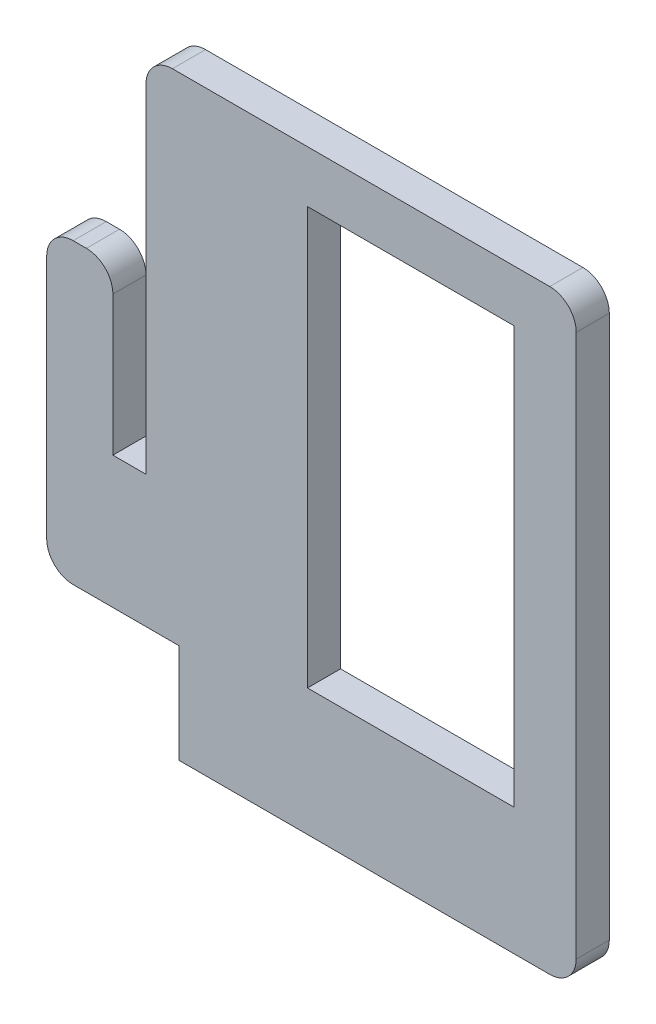
SolidWorks part; units mm, degrees
ref_plane "Front Plane" through (0, 0, 0) normal (0, 0, 1) x (1, 0, 0)
ref_plane "Top Plane" through (0, 0, 0) normal (0, 1, 0) x (1, 0, 0)
ref_plane "Right Plane" through (0, 0, 0) normal (1, 0, 0) x (0, 0, -1)
sketch "Sketch1" plane through (0, 0, 0) normal (0, 0, 1) x (1, 0, 0)
  line L1 (12.7, 0) -> (50.8, 0)
  line L2 (0, 9.525) -> (0, 38.1)
  line L3 (0, 38.1) -> (6.35, 38.1)
  line L4 (50.8, 0) -> (50.8, 38.1)
  line L5 (25.019, 52.1772) -> (44.831, 52.1772)
  line L6 (6.35, 38.1) -> (6.35, 22.1848)
  line L7 (6.35, 22.1848) -> (9.525, 22.1848)
  line L8 (9.525, 38.1) -> (9.525, 22.1848)
  line L9 (25.019, 52.1772) -> (25.019, 12.1772)
  line L10 (9.525, 38.1) -> (9.525, 57.15)
  line L11 (9.525, 57.15) -> (50.8, 57.15)
  line L12 (50.8, 38.1) -> (50.8, 57.15)
  line L13 (25.019, 12.1772) -> (44.831, 12.1772)
  line L14 (44.831, 52.1772) -> (44.831, 12.1772)
  line L15 (25.019, 52.1772) -> (44.831, 12.1772) construction
  line L16 (25.019, 12.1772) -> (44.831, 52.1772) construction
  line L19 (0, 9.525) -> (12.7, 9.525)
  line L20 (12.7, 0) -> (12.7, 9.525)
  point P11 (34.925, 32.1772)
  dimension "D2" = 50.8
  dimension "D3" = 6.35
  dimension "D4" = 3.175
  dimension "D5" = 57.15
  dimension "D6" = 25.4
  dimension "D7" = 40
  dimension "D8" = 19.812
  dimension "D9" = 10.0076
  dimension "D10" = 9.525
  dimension "D11" = 3.175
extrude "Boss-Extrude1" add sketch "Sketch1" along normal blind 3.175
fillet "Fillet2" radius 2.54 6 edges at (0, 9.525, 1.5875) (6.35, 38.1, 1.5875) (0, 38.1, 1.5875) (9.525, 57.15, 1.5875) (50.8, 0, 1.5875) (50.8, 57.15, 1.5875)
